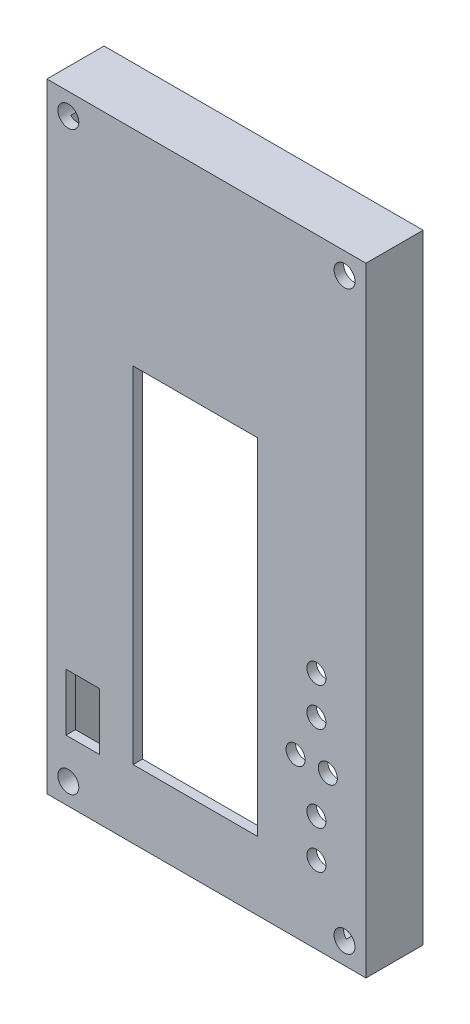
SolidWorks part; units mm, degrees
ref_plane "Front Plane" through (0, 0, 0) normal (0, 0, 1) x (1, 0, 0)
ref_plane "Top Plane" through (0, 0, 0) normal (0, 1, 0) x (1, 0, 0)
ref_plane "Right Plane" through (0, 0, 0) normal (1, 0, 0) x (0, 0, -1)
sketch "Sketch1" plane through (0, 0, 0) normal (0, 0, 1) x (1, 0, 0)
  line L0 (-33.5, -68.3325) -> (33.5, -68.3325)
  line L1 (-33.5, -68.3325) -> (-33.5, 61.6675)
  line L2 (-33.5, 61.6675) -> (33.5, 61.6675)
  line L3 (33.5, -68.3325) -> (33.5, 61.6675)
  line L4 (-30.5, -65.3325) -> (30.5, -65.3325)
  line L5 (30.5, -65.3325) -> (30.5, 58.6675)
  line L6 (-30.5, 58.6675) -> (30.5, 58.6675)
  line L7 (-30.5, -65.3325) -> (-30.5, 58.6675)
  point P8 (0, 0)
  point P9 (0, 0)
  dimension "D1" = 3
extrude "Boss-Extrude1" add sketch "Sketch1" along normal blind 10
sketch "Sketch2" plane through (0, 0, 10) normal (0, 0, 1) x (1, 0, 0)
  line L1 (-33.5, -68.3325) -> (33.5, -68.3325)
  line L2 (-33.5, -68.3325) -> (-33.5, 61.6675)
  line L3 (-33.5, 61.6675) -> (33.5, 61.6675)
  line L4 (33.5, -68.3325) -> (33.5, 61.6675)
  line L5 (-15.4, -53.9675) -> (10.7, -53.9675)
  line L6 (-15.4, -53.9675) -> (-15.4, 18.5325)
  line L7 (-15.4, 18.5325) -> (10.7, 18.5325)
  line L8 (10.7, -53.9675) -> (10.7, 18.5325)
  line L9 (-29.5, -55.6675) -> (-22.5, -55.6675)
  line L10 (-29.5, -55.6675) -> (-29.5, -43.6675)
  line L11 (-29.5, -43.6675) -> (-22.5, -43.6675)
  line L12 (-22.5, -55.6675) -> (-22.5, -43.6675)
  dimension "D1" = 18.1
  dimension "D2" = 105.335
  dimension "D3" = 117.335
  dimension "D4" = 43.135
  dimension "D5" = 115.635
extrude "Boss-Extrude2" add sketch "Sketch2" along normal blind 2
sketch "Sketch3" plane through (0, 0, 12) normal (0, 0, 1) x (1, 0, 0)
  circle A0 centre (23.0965, -52.1196) radius 2
  circle A1 centre (23.0965, -44.1155) radius 2
  circle A3 centre (18.7156, -35.0638) radius 2
  circle A4 centre (23.0964, -26.1155) radius 2
  circle A5 centre (23.0964, -18.1155) radius 2
  circle A6 centre (25.4965, -35.0661) radius 2
  point P8 (0, 0)
  point P9 (0, 0)
  point P19 (0, 0)
  point P21 (0, 0)
  point P22 (0, 0)
  point P23 (0, 0)
extrude "Cut-Extrude1" cut sketch "Sketch3" against normal through all
sketch "Sketch4" plane through (0, 0, 12) normal (0, 0, 1) x (1, 0, 0)
  line L0 (-33.5, 61.6675) -> (-33.5, -68.3325) construction
  line L1 (33.5, 61.6675) -> (-33.5, 61.6675) construction
  line L3 (33.5, -68.3325) -> (33.5, 61.6675) construction
  line L4 (-33.5, -68.3325) -> (33.5, -68.3325) construction
  circle A0 centre (-29, 57.1675) radius 2.2
  circle A1 centre (29, 57.1675) radius 2.2
  circle A2 centre (-29, -63.8325) radius 2.2
  circle A3 centre (29, -63.8325) radius 2.2
  dimension "D1" = 4.5
  dimension "D5" = 4.5
  dimension "D2" = 4.5
  dimension "D3" = 4.5
  dimension "D4" = 4.5
extrude "Cut-Extrude2" cut sketch "Sketch4" against normal through all
